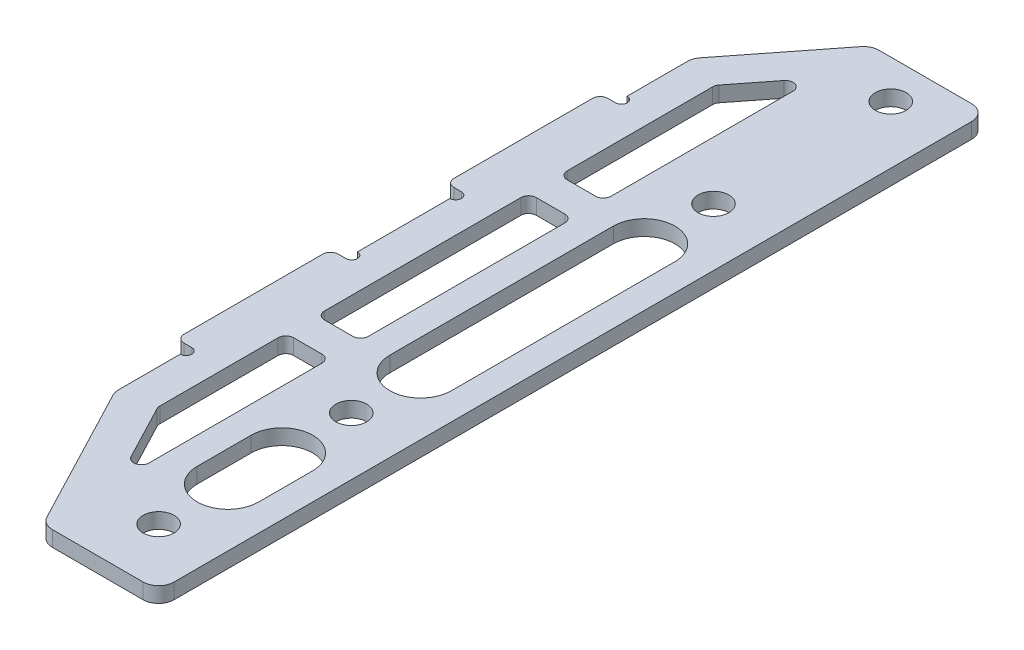
SolidWorks part; units mm, degrees
material "Thornel Mat VMA"
ref_plane "前视基准面" through (0, 0, 0) normal (0, 0, 1) x (1, 0, 0)
ref_plane "上视基准面" through (0, 0, 0) normal (0, 1, 0) x (1, 0, 0)
ref_plane "右视基准面" through (0, 0, 0) normal (1, 0, 0) x (0, 0, -1)
sketch "草图1" plane through (0, 0, 0) normal (0, 1, 0) x (1, 0, 0)
  line L0 (7.5, 100) -> (7.5, -7.5)
  line L2 (0, 0) -> (0, 100) construction
  line L5 (0, 0) -> (5.3596, 0) construction
  line L6 (-17.7, 57) -> (-17.7, 42)
  line L7 (-17.7, 77) -> (-19.7, 77)
  line L9 (-7.5, 100) -> (7.5, 100)
  line L10 (-17.7, 87) -> (-17.7, 77)
  line L11 (-7.5, -7.5) -> (7.5, -7.5)
  line L12 (-17.7, 57) -> (-19.7, 57)
  line L13 (-19.7, 77) -> (-19.7, 57)
  line L14 (-7.5, 100) -> (-17.7, 87)
  line L15 (-7.5, -7.5) -> (-17.7, 12)
  line L16 (-17.7, 22) -> (-17.7, 12)
  line L17 (-17.7, 42) -> (-19.7, 42)
  line L19 (-17.7, 22) -> (-19.7, 22)
  line L20 (-19.7, 42) -> (-19.7, 22)
  circle A0 centre (0, 25) radius 2
  circle A1 centre (0, 0) radius 2
  circle A2 centre (0, 72) radius 2
  circle A4 centre (0, 95) radius 2
  dimension "D4" = 7.5
  dimension "D3" = 4
  dimension "D5" = 47
  dimension "D7" = 23
  dimension "D10" = 5
  dimension "D1" = 25
  dimension "D2" = 25.2
  dimension "D6" = 19.5
  dimension "D8" = 20
  dimension "D9" = 2
  dimension "D11" = 15
  dimension "D12" = 15
  dimension "D13" = 10
  dimension "D14" = 10
extrude "凸台-拉伸1" add sketch "草图1" along normal blind 2
sketch "草图2" plane through (0, 2, 0) normal (0, 1, 0) x (1, 0, 0)
  line L0 (-17.7, 87) -> (-17.7, 77) construction
  line L1 (-17.7, 57) -> (-17.7, 42) construction
  line L2 (-17.7, 22) -> (-17.7, 12) construction
  circle A0 centre (-17.7, 77.75) radius 0.75
  circle A1 centre (-17.7, 56.25) radius 0.75
  circle A2 centre (-17.7, 42.75) radius 0.75
  circle A3 centre (-17.7, 21.25) radius 0.75
  dimension "D1" = 1.5
extrude "切除-拉伸1" cut sketch "草图2" against normal through all
fillet "圆角1" radius 2 6 edges at (7.5, 1, -100) (7.5, 1, 7.5) (-7.5, 1, 7.5) (-17.7, 1, -87) (-7.5, 1, -100) (-17.7, 1, -12)
sketch "草图3" plane through (0, 2, 0) normal (0, 1, 0) x (1, 0, 0)
  line L3 (0, 9) -> (0, 16) construction
  line L4 (-4, 9) -> (-4, 16)
  line L5 (4, 9) -> (4, 16)
  line L6 (0, 63) -> (0, 34) construction
  line L7 (4, 63) -> (4, 34)
  line L8 (-4, 63) -> (-4, 34)
  line L9 (-7.5, 92.71) -> (-13.2, 85.4453)
  line L10 (-13.2, 85.4453) -> (-13.2, 65.2096)
  line L11 (-13.2, 13.1058) -> (-7.5, 2.2088)
  line L12 (-7.5, 2.2088) -> (-7.5, 29.7092)
  line L14 (-17.7, 55.5) -> (-17.7, 43.5) construction
  line L15 (-8.1006, 99.2346) -> (-17.2735, 87.5436) construction
  line L16 (-17.4722, 11.5645) -> (-8.0613, -6.427) construction
  line L17 (-13.2, 65.2096) -> (-7.5, 65.2096)
  line L18 (-13.2, 61.2096) -> (-7.5, 61.2096)
  line L19 (-13.2, 33.7092) -> (-7.5, 33.7092)
  line L20 (-13.2, 29.7092) -> (-7.5, 29.7092)
  line L21 (-7.5, 33.7092) -> (-7.5, 61.2096)
  line L22 (-13.2, 29.7092) -> (-13.2, 13.1058)
  line L23 (-13.2, 61.2096) -> (-13.2, 33.7092)
  line L24 (-7.5, 65.2096) -> (-7.5, 92.71)
  arc A0 (-4, 9) -> (4, 9) centre (0, 9) ccw
  arc A1 (4, 16) -> (-4, 16) centre (0, 16) ccw
  arc A2 (4, 63) -> (-4, 63) centre (0, 63) ccw
  arc A3 (-4, 34) -> (4, 34) centre (0, 34) ccw
  circle A4 centre (0, 0) radius 2 construction
  circle A5 centre (0, 25) radius 2 construction
  circle A6 centre (0, 72) radius 2 construction
  point P2 (0, 12.5)
  point P8 (0, 48.5)
  point P22 (0, 5)
  point P23 (0, 20)
  point P26 (0, 30)
  point P27 (0, 67)
  dimension "D2" = 5
  dimension "D4" = 5
  dimension "D1" = 8
  dimension "D3" = 5
  dimension "D5" = 5
  dimension "D6" = 3.5
  dimension "D7" = 4.5
  dimension "D8" = 4.5
  dimension "D9" = 4.5
  dimension "D10" = 4
  dimension "D11" = 4
extrude "切除-拉伸2" cut sketch "草图3" against normal through all
fillet "圆角2" radius 1 16 edges at (-19.7, 1, -22) (-19.7, 1, -42) (-19.7, 1, -57) (-19.7, 1, -77) (-13.2, 1, -61.2096) (-7.5, 1, -61.2096) (-7.5, 1, -33.7092) (-13.2, 1, -33.7092) (-7.5, 1, -2.2088) (-13.2, 1, -13.1058) (-13.2, 1, -29.7092) (-7.5, 1, -29.7092) (-7.5, 1, -65.2096) (-13.2, 1, -85.4453) (-7.5, 1, -92.71) (-13.2, 1, -65.2096)
